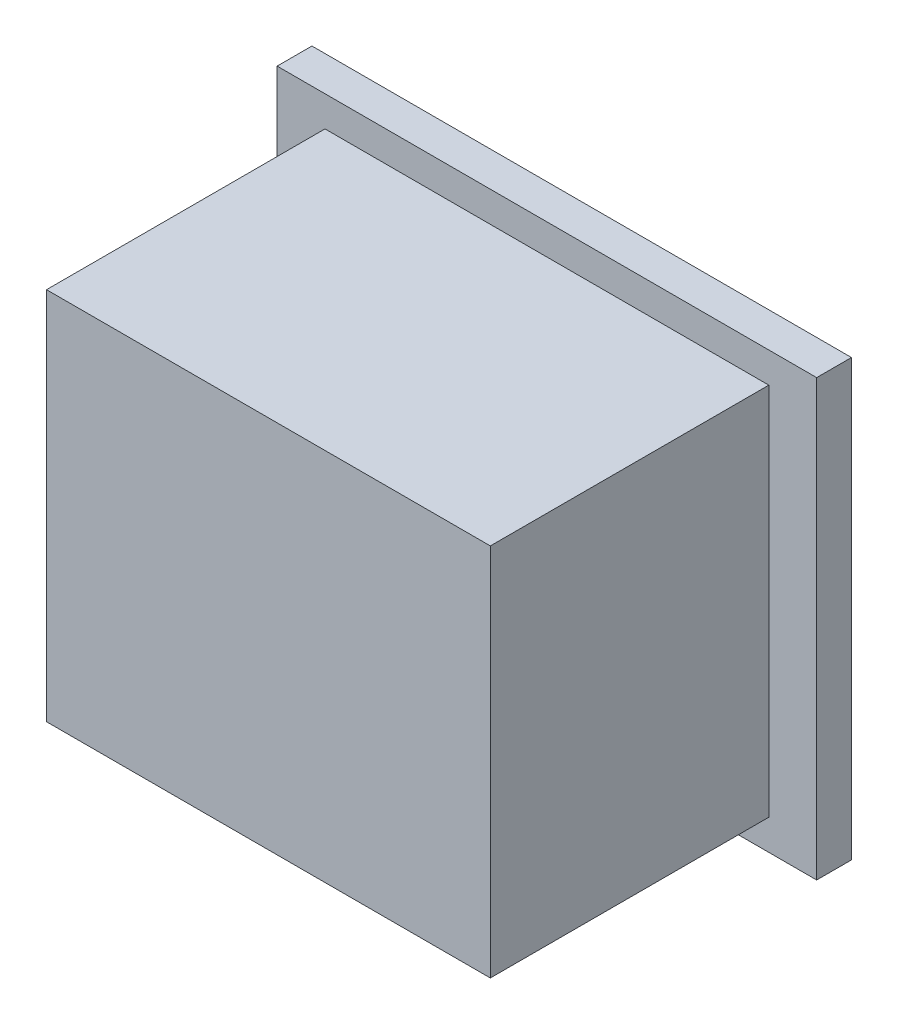
SolidWorks part; units mm, degrees
ref_plane "Front Plane" through (0, 0, 0) normal (0, 0, 1) x (1, 0, 0)
ref_plane "Top Plane" through (0, 0, 0) normal (0, 1, 0) x (1, 0, 0)
ref_plane "Right Plane" through (0, 0, 0) normal (1, 0, 0) x (0, 0, -1)
sketch "Sketch1" plane through (0, 0, 0) normal (0, 0, 1) x (1, 0, 0)
  line L1 (12.75, -10.75) -> (-12.75, -10.75)
  line L2 (12.75, -10.75) -> (12.75, 10.75)
  line L3 (12.75, 10.75) -> (-12.75, 10.75)
  line L4 (-12.75, -10.75) -> (-12.75, 10.75)
  line L5 (12.75, -10.75) -> (-12.75, 10.75) construction
  line L6 (12.75, 10.75) -> (-12.75, -10.75) construction
  point P0 (0, 0)
  dimension "D1" = 21.5
  dimension "D2" = 25.5
extrude "Boss-Extrude1" add sketch "Sketch1" along normal blind 16
sketch "Sketch2" plane through (0, 0, 0) normal (0, 0, -1) x (-1, 0, 0)
  line L1 (15.5, -12.5) -> (-15.5, -12.5)
  line L2 (15.5, -12.5) -> (15.5, 12.5)
  line L3 (15.5, 12.5) -> (-15.5, 12.5)
  line L4 (-15.5, -12.5) -> (-15.5, 12.5)
  line L5 (15.5, -12.5) -> (-15.5, 12.5) construction
  line L6 (15.5, 12.5) -> (-15.5, -12.5) construction
  point P0 (0, 0)
  dimension "D1" = 25
  dimension "D2" = 31
extrude "Boss-Extrude2" add sketch "Sketch2" along normal blind 2
